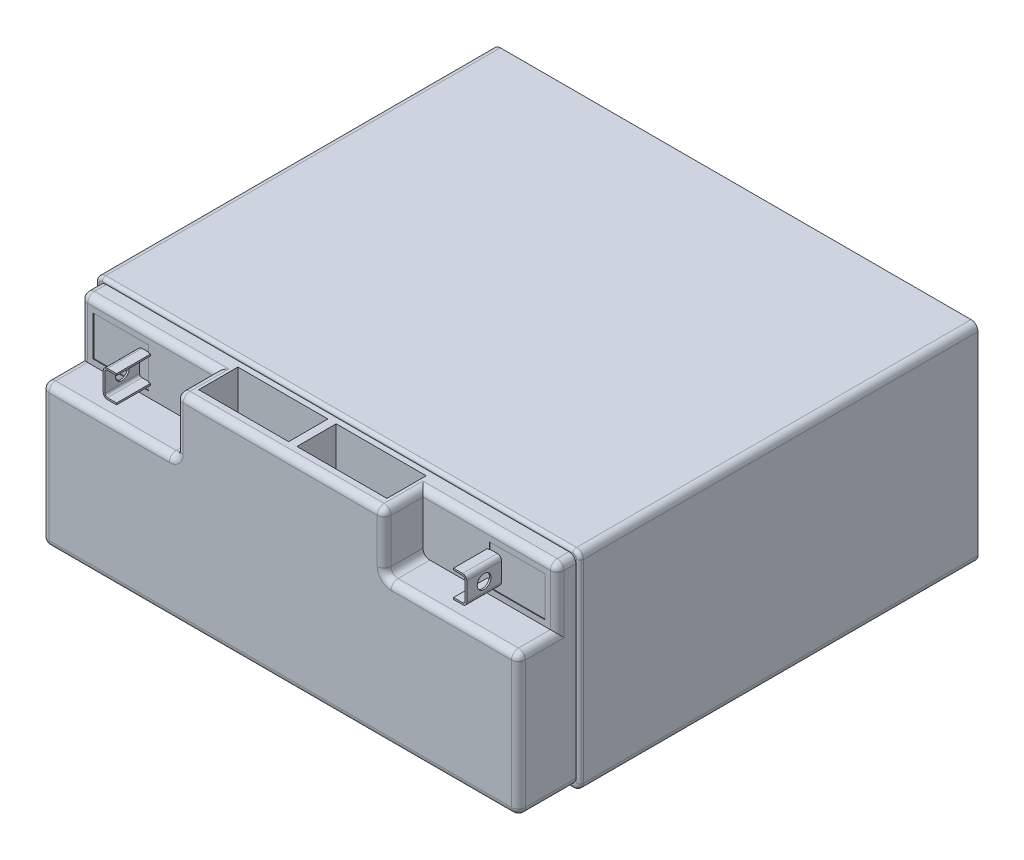
SolidWorks part; units mm, degrees
ref_plane "Front Plane" through (0, 0, 0) normal (0, 0, 1) x (1, 0, 0)
ref_plane "Top Plane" through (0, 0, 0) normal (0, 1, 0) x (1, 0, 0)
ref_plane "Right Plane" through (0, 0, 0) normal (1, 0, 0) x (0, 0, -1)
ref_plane "Plane1" through (0, -62.2132, 0) normal (0, -1, 0) x (1, 0, 0)
sketch "Sketch1" plane through (0, -62.2132, 0) normal (0, -1, 0) x (1, 0, 0)
  line L0 (-33.1131, 0) -> (144.6869, 0)
  line L1 (144.6869, 0) -> (144.6869, 146.05)
  line L2 (144.6869, 146.05) -> (-33.1131, 146.05)
  line L3 (-33.1131, 146.05) -> (-33.1131, 0)
extrude "Boss-Extrude1" add sketch "Sketch1" against normal blind 76.2
sketch "Sketch2" plane through (0, 0, 146.05) normal (0, 0, 1) x (1, 0, 0)
  line L0 (143.2096, 12.5094) -> (143.2096, -60.7358)
  line L1 (143.2096, -60.7358) -> (-31.6357, -60.7358)
  line L2 (-31.6357, -60.7358) -> (-31.6357, 12.5094)
  line L3 (-31.6357, 12.5094) -> (143.2096, 12.5094)
extrude "Boss-Extrude2" add sketch "Sketch2" along normal blind 21.082
sketch "Sketch3" plane through (-31.6357, 0, 0) normal (-1, 0, 0) x (0, 0, 1)
  line L0 (152.908, 12.5094) -> (152.908, -8.8266)
  line L1 (152.908, -8.8266) -> (167.132, -8.8266)
  line L2 (167.132, -8.8266) -> (167.132, 12.5094)
  line L3 (167.132, 12.5094) -> (152.908, 12.5094)
extrude "Cut-Extrude1" cut sketch "Sketch3" against normal blind 49.276
sketch "Sketch4" plane through (0, 0, 152.908) normal (0, 0, 1) x (1, 0, 0)
  line L0 (-27.0726, 7.9428) -> (-27.0726, -6.6776)
  line L1 (-27.0726, -6.6776) -> (-6.7872, -6.6776)
  line L2 (-6.7872, -6.6776) -> (-6.7872, -4.5374)
  line L3 (-6.7872, -4.5374) -> (-10.918, -4.5374)
  line L4 (-10.918, -4.5374) -> (-10.918, 5.3949)
  line L5 (-10.918, 5.3949) -> (-6.7872, 5.3949)
  line L6 (-6.7872, 5.3949) -> (-6.7872, 7.9428)
  line L7 (-6.7872, 7.9428) -> (-27.0726, 7.9428)
extrude "Cut-Extrude2" cut sketch "Sketch4" against normal blind 0.254
sketch "Sketch5" plane through (0, 0, 152.908) normal (0, 0, 1) x (1, 0, 0)
  line L0 (-6.018, -4.5374) -> (-10.918, -4.5374)
  line L1 (-10.918, -4.5374) -> (-10.918, 5.3949)
  line L2 (-10.918, 5.3949) -> (-6.018, 5.3949)
  line L3 (-6.018, 5.3949) -> (-6.018, -4.5374)
extrude "Boss-Extrude3" add sketch "Sketch5" along normal blind 12.446
sketch "Sketch6" plane through (-6.018, 0, 0) normal (1, 0, 0) x (0, 0, -1)
  line L0 (-152.908, -3.9265) -> (-152.908, 4.784)
  line L1 (-152.908, 4.784) -> (-165.354, 4.784)
  line L2 (-165.354, 4.784) -> (-165.354, -3.9265)
  line L3 (-165.354, -3.9265) -> (-152.908, -3.9265)
extrude "Cut-Extrude3" cut sketch "Sketch6" against normal blind 4.289
sketch "Sketch7" plane through (0, 0, 152.908) normal (0, 0, 1) x (1, 0, 0)
  line L0 (-10.3071, 4.784) -> (-10.3071, -3.9265)
  line L1 (-10.3071, -3.9265) -> (-6.7872, -3.9265)
  line L2 (-6.7872, -3.9265) -> (-6.7872, 4.784)
  line L3 (-6.7872, 4.784) -> (-10.3071, 4.784)
extrude "Cut-Extrude4" cut sketch "Sketch7" against normal blind 0.254
sketch "Sketch8" plane through (0, 12.5094, 0) normal (0, 1, 0) x (-1, 0, 0)
  line L0 (-143.2096, 152.908) -> (-93.9336, 152.908)
  line L1 (-93.9336, 152.908) -> (-93.9336, 167.132)
  line L2 (-93.9336, 167.132) -> (-143.2096, 167.132)
  line L3 (-143.2096, 167.132) -> (-143.2096, 152.908)
extrude "Cut-Extrude5" cut sketch "Sketch8" against normal blind 21.336
sketch "Sketch9" plane through (0, 0, 152.908) normal (0, 0, 1) x (1, 0, 0)
  line L0 (118.361, 5.3949) -> (122.4919, 5.3949)
  line L1 (122.4919, 5.3949) -> (122.4919, -4.5374)
  line L2 (122.4919, -4.5374) -> (118.361, -4.5374)
  line L3 (118.361, -4.5374) -> (118.361, -6.6776)
  line L4 (118.361, -6.6776) -> (138.6465, -6.6776)
  line L5 (138.6465, -6.6776) -> (138.6465, 7.9428)
  line L6 (138.6465, 7.9428) -> (118.361, 7.9428)
  line L7 (118.361, 7.9428) -> (118.361, 5.3949)
extrude "Cut-Extrude6" cut sketch "Sketch9" against normal blind 0.254
sketch "Sketch10" plane through (0, 0, 152.908) normal (0, 0, 1) x (1, 0, 0)
  line L0 (122.4919, -4.5374) -> (117.5919, -4.5374)
  line L1 (117.5919, -4.5374) -> (117.5919, 5.3949)
  line L2 (117.5919, 5.3949) -> (122.4919, 5.3949)
  line L3 (122.4919, 5.3949) -> (122.4919, -4.5374)
extrude "Boss-Extrude4" add sketch "Sketch10" along normal blind 12.446
sketch "Sketch11" plane through (117.5919, 0, 0) normal (-1, 0, 0) x (0, 0, 1)
  line L0 (152.908, 4.784) -> (152.908, -3.9265)
  line L1 (152.908, -3.9265) -> (165.354, -3.9265)
  line L2 (165.354, -3.9265) -> (165.354, 4.784)
  line L3 (165.354, 4.784) -> (152.908, 4.784)
extrude "Cut-Extrude7" cut sketch "Sketch11" against normal blind 4.289
sketch "Sketch12" plane through (0, 0, 152.908) normal (0, 0, 1) x (1, 0, 0)
  line L0 (121.8809, 4.784) -> (118.361, 4.784)
  line L1 (118.361, 4.784) -> (118.361, -3.9265)
  line L2 (118.361, -3.9265) -> (121.8809, -3.9265)
  line L3 (121.8809, -3.9265) -> (121.8809, 4.784)
extrude "Cut-Extrude8" cut sketch "Sketch12" against normal blind 0.254
sketch "Sketch13" plane through (0, 12.5094, 0) normal (0, 1, 0) x (-1, 0, 0)
  line L0 (-90.3309, 148.1138) -> (-57.3109, 148.1138)
  line L1 (-57.3109, 148.1138) -> (-57.3109, 162.5135)
  line L2 (-57.3109, 162.5135) -> (-90.3309, 162.5135)
  line L3 (-90.3309, 162.5135) -> (-90.3309, 148.1138)
extrude "Cut-Extrude9" cut sketch "Sketch13" against normal blind 19.05
sketch "Sketch14" plane through (0, 12.5094, 0) normal (0, 1, 0) x (-1, 0, 0)
  line L0 (-54.2629, 148.1138) -> (-21.2429, 148.1138)
  line L1 (-21.2429, 148.1138) -> (-21.2429, 162.5135)
  line L2 (-21.2429, 162.5135) -> (-54.2629, 162.5135)
  line L3 (-54.2629, 162.5135) -> (-54.2629, 148.1138)
extrude "Cut-Extrude10" cut sketch "Sketch14" against normal blind 19.05
sketch "Sketch15" plane through (0, -60.7358, 0) normal (0, -1, 0) x (1, 0, 0)
  line L0 (56.8496, 162.8434) -> (56.8496, 147.6421)
  line L1 (56.8496, 147.6421) -> (120.3496, 147.6421)
  line L2 (120.3496, 147.6421) -> (120.3496, 162.8434)
  line L3 (120.3496, 162.8434) -> (56.8496, 162.8434)
extrude "Cut-Extrude11" cut sketch "Sketch15" against normal blind 19.558
sketch "Sketch16" plane through (0, -60.7358, 0) normal (0, -1, 0) x (1, 0, 0)
  line L0 (-8.7757, 162.8434) -> (-8.7757, 147.6421)
  line L1 (-8.7757, 147.6421) -> (54.7243, 147.6421)
  line L2 (54.7243, 147.6421) -> (54.7243, 162.8434)
  line L3 (54.7243, 162.8434) -> (-8.7757, 162.8434)
extrude "Cut-Extrude12" cut sketch "Sketch16" against normal blind 19.558
hole_wizard "Hole1" positions "Sketch18" profile "Sketch17" legacy
sketch "Sketch18" plane through (122.4919, 0, 0) normal (1, 0, 0) x (0, 0, -1)
  point P0 (-159.004, 0.4288)
sketch "Sketch17" plane through (122.4919, 0.4288, 159.004) normal (0, 1, 0) x (0, 0, -1)
  line L0 (0, 0) -> (0, 0.6109)
  line L1 (0, 0.6109) -> (2.54, 0.6109)
  line L2 (2.54, 0.6109) -> (2.54, 0)
  line L3 (2.54, 0) -> (0, 0)
  line L4 (0, 110) -> (0, -10) construction
  dimension "Diameter" = 5.08
  dimension "Depth" = 0.6109
hole_wizard "Hole2" positions "Sketch20" profile "Sketch19" legacy
sketch "Sketch20" plane through (-10.3071, 0, 0) normal (1, 0, 0) x (0, 0, -1)
  point P0 (-159.004, 0.4288)
sketch "Sketch19" plane through (-10.3071, 0.4288, 159.004) normal (0, 1, 0) x (0, 0, -1)
  line L0 (0, 0) -> (0, 22.806)
  line L1 (0, 22.806) -> (2.54, 22.806)
  line L2 (2.54, 22.806) -> (2.54, 0)
  line L3 (2.54, 0) -> (0, 0)
  line L4 (0, 110) -> (0, -10) construction
  dimension "Diameter" = 5.08
  dimension "Depth" = 22.806
fillet "Fillet1" radius 2.54 26 edges at (143.2096, -60.7358, 156.591) (143.2096, 12.5094, 149.479) (143.2096, 1.8414, 152.908) (-31.6357, -60.7358, 156.591) (55.7869, -60.7358, 167.132) (143.2096, -34.7812, 167.132) (143.2096, -8.8266, 160.02) (118.5716, 12.5094, 152.908) (-31.6357, 12.5094, 149.479) (-31.6357, 1.8414, 152.908) (-31.6357, -8.8266, 160.02) (-31.6357, -34.7812, 167.132) (93.9336, 1.8414, 167.132) (118.5716, -8.8266, 167.132) (93.9336, 12.5094, 160.02) (-6.9977, 12.5094, 152.908) (17.6403, 1.8414, 167.132) (-6.9977, -8.8266, 167.132) (55.7869, 12.5094, 167.132) (17.6403, 12.5094, 160.02) (17.6403, -8.8266, 160.02) (-33.1131, 13.9868, 73.025) (93.9336, -8.8266, 160.02) (144.6869, -62.2132, 73.025) (-33.1131, -62.2132, 73.025) (144.6869, 13.9868, 73.025)
fillet "Fillet2" radius 0.9131 4 edges at (121.8809, -3.9265, 159.004) (-10.3071, 4.784, 159.004) (121.8809, 4.784, 159.004) (-10.3071, -3.9265, 159.004)
fillet "Fillet3" radius 1.27 8 edges at (143.943, 13.2428, 146.05) (55.7869, 13.9868, 146.05) (144.6869, -24.1132, 146.05) (-32.3691, 13.2428, 146.05) (143.943, -61.4693, 146.05) (-33.1131, -24.1132, 146.05) (55.7869, -62.2132, 146.05) (-32.3691, -61.4693, 146.05)
fillet "Fillet4" radius 1.524 4 edges at (122.4919, 5.3949, 159.004) (-10.918, -4.5374, 159.004) (122.4919, -4.5374, 159.004) (-10.918, 5.3949, 159.004)
